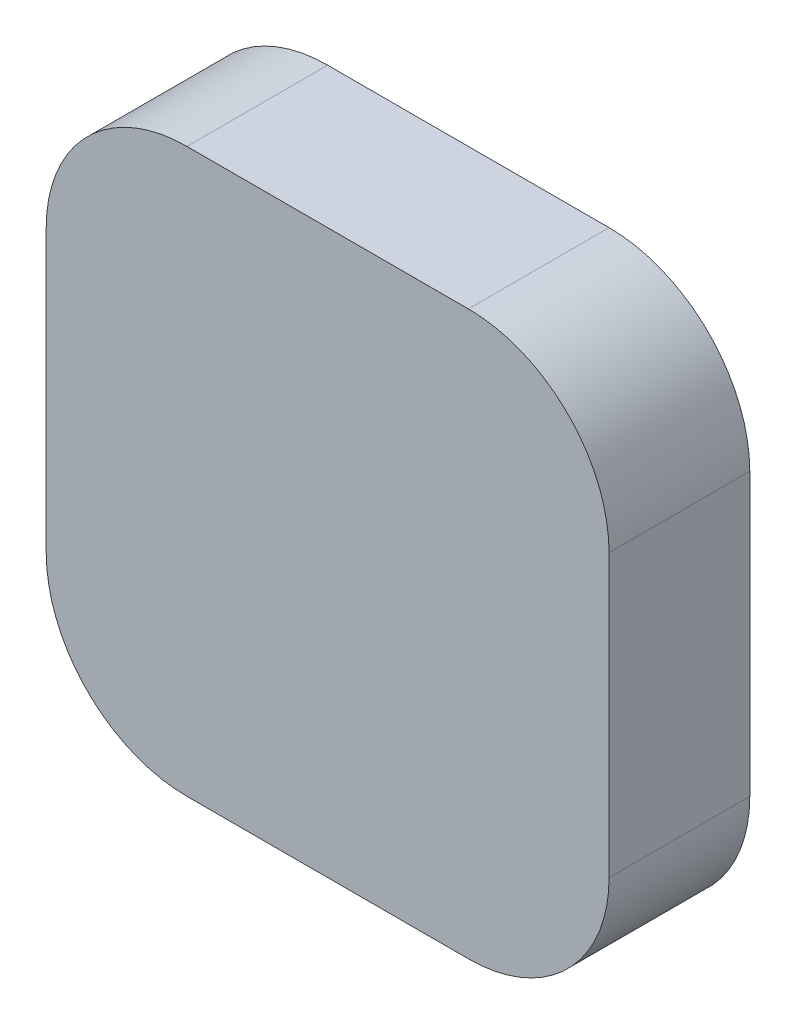
SolidWorks part; units mm, degrees
ref_plane "Front Plane" through (0, 0, 0) normal (0, 0, 1) x (1, 0, 0)
ref_plane "Top Plane" through (0, 0, 0) normal (0, 1, 0) x (1, 0, 0)
ref_plane "Right Plane" through (0, 0, 0) normal (1, 0, 0) x (0, 0, -1)
sketch "Sketch1" plane through (0, 0, 0) normal (0, 0, 1) x (1, 0, 0)
  line L1 (0, 0) -> (20, 0)
  line L2 (0, 0) -> (0, 20)
  line L3 (0, 20) -> (20, 20)
  line L4 (20, 0) -> (20, 20)
extrude "Boss-Extrude1" add sketch "Sketch1" along normal blind 5
fillet "Fillet1" radius 5 4 edges at (20, 0, 2.5) (0, 0, 2.5) (0, 20, 2.5) (20, 20, 2.5)
